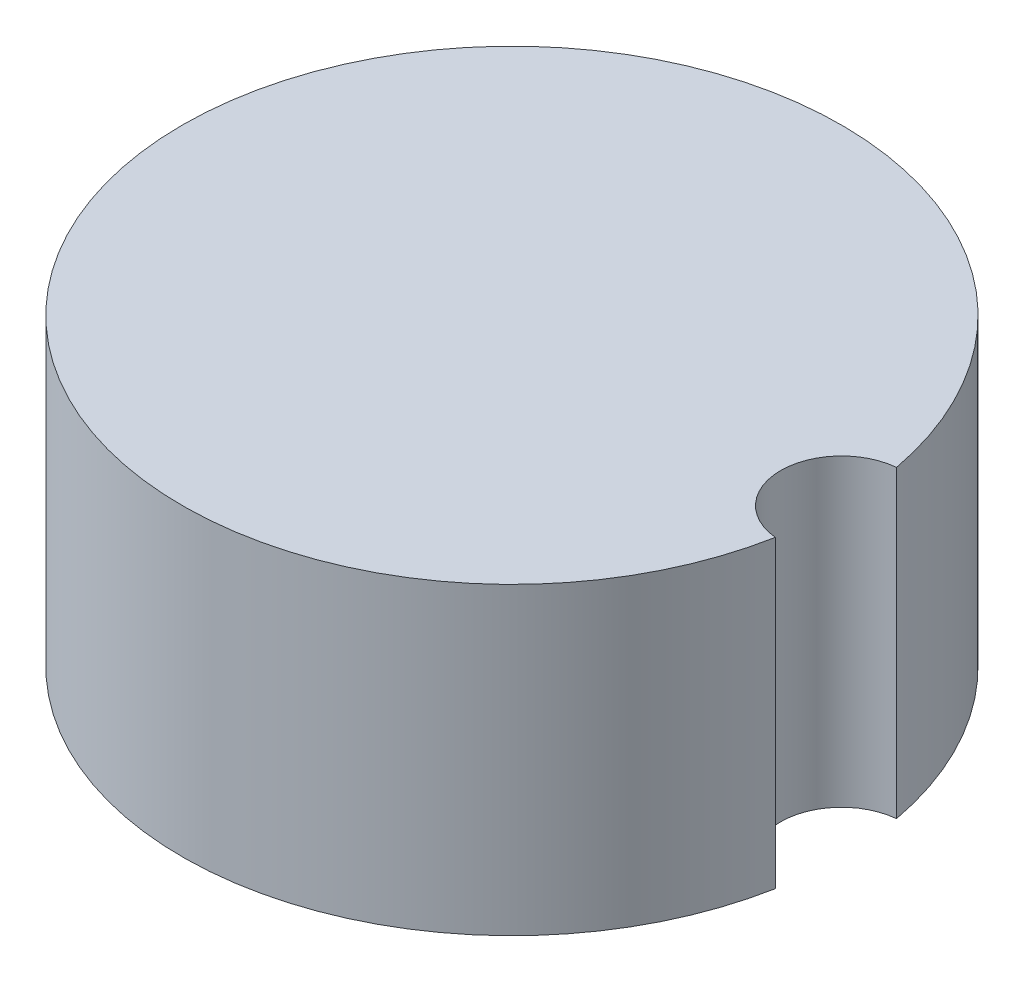
SolidWorks part; units mm, degrees
ref_plane "Front Plane" through (0, 0, 0) normal (0, 0, 1) x (1, 0, 0)
ref_plane "Top Plane" through (0, 0, 0) normal (0, 1, 0) x (1, 0, 0)
ref_plane "Right Plane" through (0, 0, 0) normal (1, 0, 0) x (0, 0, -1)
sketch "Sketch1" plane through (0, 75, 0) normal (0, 1, 0) x (1, 0, 0)
  arc A0 (6.3892, 1.1949) -> (6.3892, -1.1949) centre (6.5, 0) ccw construction
  arc A1 (6.3892, 1.1949) -> (6.3892, -1.1949) centre (0, 0) ccw construction
  arc A2 (6.3892, 1.1949) -> (6.3892, -1.1949) centre (6.5, 0) ccw
  arc A3 (6.3892, 1.1949) -> (6.3892, -1.1949) centre (0, 0) ccw
extrude "Boss-Extrude1" add sketch "Sketch1" along normal blind 6
